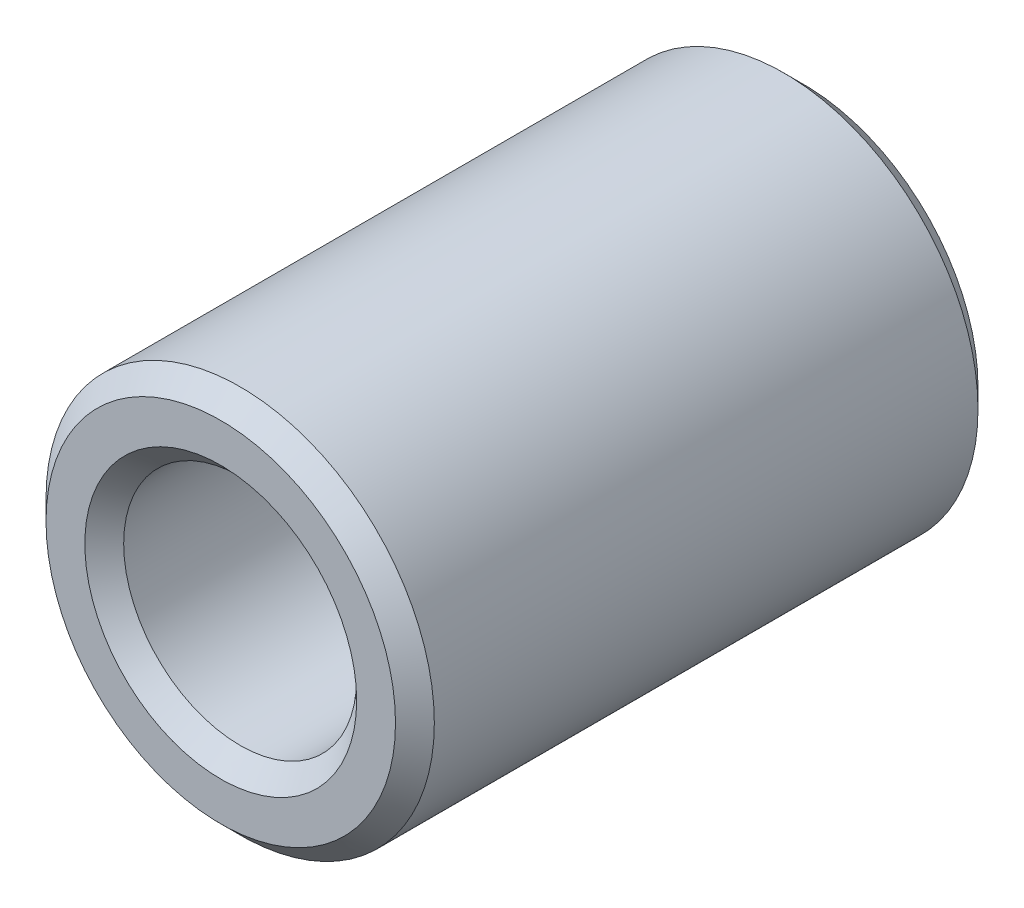
SolidWorks part; units mm, degrees
material "Литая легированная сталь"
ref_plane "Спереди" through (0, 0, 0) normal (0, 0, 1) x (1, 0, 0)
ref_plane "Сверху" through (0, 0, 0) normal (0, 1, 0) x (1, 0, 0)
ref_plane "Справа" through (0, 0, 0) normal (1, 0, 0) x (0, 0, -1)
other "Configuration Table"
sketch "Эскиз1" plane through (0, 0, 0) normal (0, 0, 1) x (1, 0, 0)
  circle A0 centre (0, 0) radius 3
  circle A1 centre (0, 0) radius 5
  dimension "D1" = 6
  dimension "D2" = 10
extrude "Бобышка-Вытянуть1" add sketch "Эскиз1" along normal blind 15
chamfer "Фаска1" distance 0.5 angle 45 4 edges at (3, 0, 0) (5, 0, 0) (3, 0, 15) (5, 0, 15)
